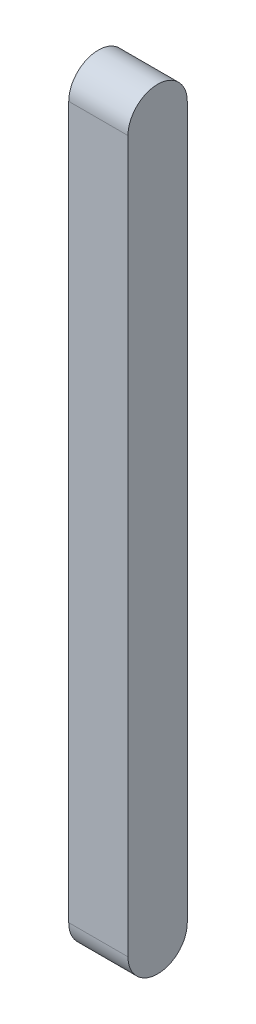
SolidWorks part; units mm, degrees
material "ABS"
ref_plane "前视基准面" through (0, 0, 0) normal (0, 0, 1) x (1, 0, 0)
ref_plane "上视基准面" through (0, 0, 0) normal (0, 1, 0) x (1, 0, 0)
ref_plane "右视基准面" through (0, 0, 0) normal (1, 0, 0) x (0, 0, -1)
sketch "草图1" plane through (0, 0, 0) normal (1, 0, 0) x (0, 0, -1)
  line L1 (-5, 60) -> (5, 60)
  line L2 (-5, 60) -> (-5, -60)
  line L3 (-5, -60) -> (5, -60)
  line L4 (5, 60) -> (5, -60)
  line L5 (-5, 60) -> (5, -60) construction
  line L6 (-5, -60) -> (5, 60) construction
  circle A0 centre (0, 60) radius 5
  circle A1 centre (0, -60) radius 5
  point P0 (0, 0)
extrude "凸台-拉伸1" add sketch "草图1" along normal blind 10 contours L3 A1 | A0
